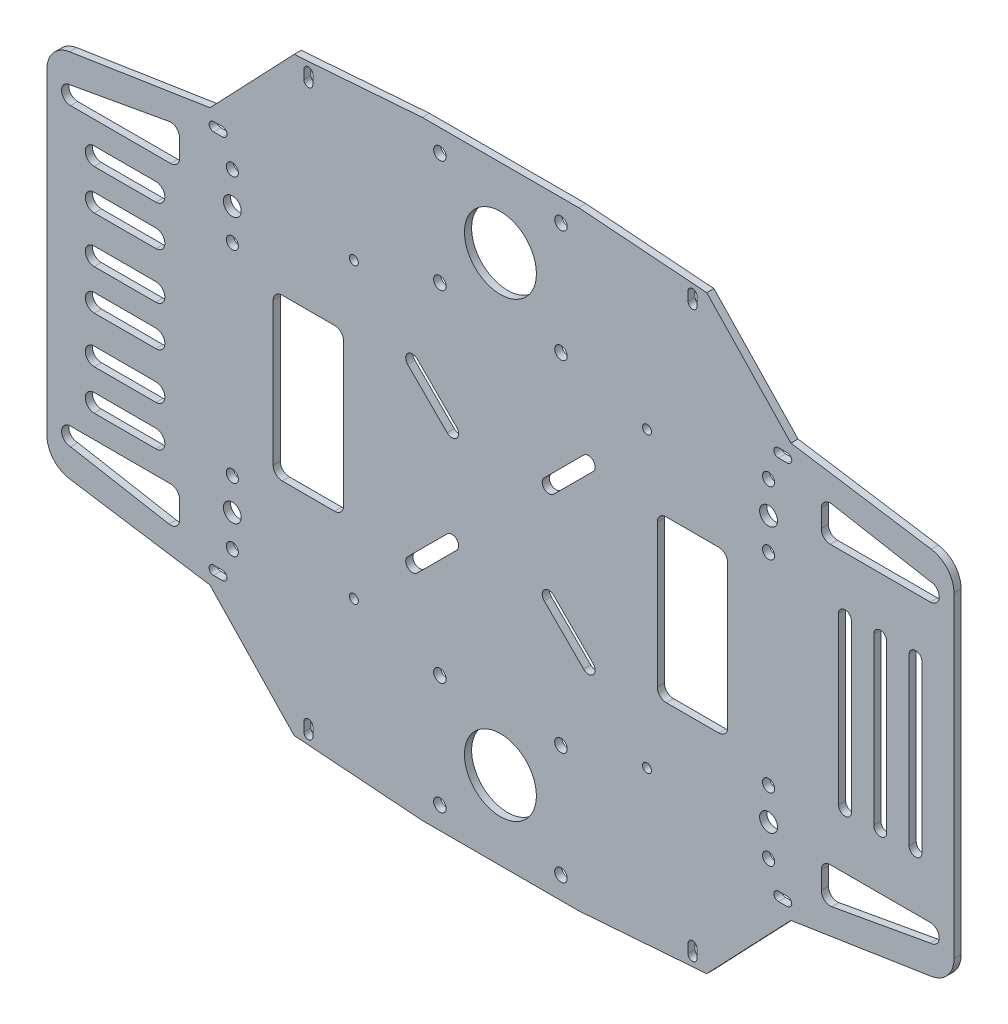
SolidWorks part; units mm, degrees
ref_plane "Front Plane" through (0, 0, 0) normal (0, 0, 1) x (1, 0, 0)
ref_plane "Top Plane" through (0, 0, 0) normal (0, 1, 0) x (1, 0, 0)
ref_plane "Right Plane" through (0, 0, 0) normal (1, 0, 0) x (0, 0, -1)
sketch "Sketch1" plane through (0, 0, 0) normal (0, 0, 1) x (1, 0, 0)
  line L0 (0, 0) -> (0, 68.13) construction
  line L5 (71.9943, -68.13) -> (-71.9943, 68.13) construction
  line L6 (71.9943, 68.13) -> (-71.9943, -68.13) construction
  line L7 (0, 0) -> (0, -68.13) construction
  line L8 (0, 68.13) -> (-46.175, 68.13) construction
  line L9 (0, 68.13) -> (46.175, 68.13) construction
  line L10 (0, 0) -> (46.175, 0) construction
  line L11 (0, 0) -> (-46.175, 0) construction
  line L12 (46.175, 0) -> (46.175, 66) construction
  line L13 (-46.175, 0) -> (-46.175, 66) construction
  line L14 (0, -68.13) -> (-46.175, -68.13) construction
  line L15 (0, -68.13) -> (46.175, -68.13) construction
  line L16 (-46.175, 0) -> (-46.175, -66) construction
  line L17 (46.175, 0) -> (46.175, -66) construction
  line L18 (0, 68.13) -> (-17.5, 68.13)
  line L19 (0, 68.13) -> (17.5, 68.13)
  line L20 (-17.5, 68.13) -> (-46.175, 66)
  line L21 (17.5, 68.13) -> (46.175, 66)
  line L22 (0, -68.13) -> (-17.5, -68.13)
  line L23 (-17.5, -68.13) -> (-46.175, -66)
  line L24 (0, -68.13) -> (17.5, -68.13)
  line L25 (17.5, -68.13) -> (46.175, -66)
  line L26 (46.175, 0) -> (65, 0) construction
  line L27 (-46.175, 0) -> (-65, 0) construction
  line L28 (65, 0) -> (65, 46.25) construction
  line L29 (65, 0) -> (65, -46.25) construction
  line L31 (46.175, -66) -> (65, -46.25)
  line L32 (-65, 0) -> (-65, 46.25) construction
  line L33 (-46.175, 66) -> (-65, 46.25)
  line L34 (-65, 0) -> (-65, -46.25) construction
  line L35 (-65, -46.25) -> (-46.175, -66)
  line L36 (65, 0) -> (101.5, 0) construction
  line L37 (-65, 0) -> (-101.5, 0) construction
  line L38 (-101.5, 0) -> (-101.5, 35.4573)
  line L39 (-65, 46.25) -> (-96.4178, 41.3867)
  line L40 (-101.5, 0) -> (-101.5, -35.4573)
  line L41 (-96.4178, -41.3867) -> (-65, -46.25)
  line L42 (101.5, 0) -> (101.5, 35.4573)
  line L43 (101.5, 0) -> (101.5, -35.4573)
  line L44 (96.4178, -41.3867) -> (65, -46.25)
  line L45 (65, 46.25) -> (96.4178, 41.3867)
  line L46 (46.175, 66) -> (65, 46.25)
  arc A0 (96.4178, -41.3867) -> (101.5, -35.4573) centre (95.5, -35.4573) ccw
  arc A1 (101.5, 35.4573) -> (96.4178, 41.3867) centre (95.5, 35.4573) ccw
  arc A2 (-96.4178, -41.3867) -> (-101.5, -35.4573) centre (-95.5, -35.4573) cw
  arc A3 (-101.5, 35.4573) -> (-96.4178, 41.3867) centre (-95.5, 35.4573) cw
  point P0 (0, 0)
  point P41 (-101.5, -40.6)
  point P44 (-101.5, 40.6)
  dimension "D16" = 6
  dimension "D17" = 6
  dimension "D18" = 6
  dimension "D19" = 6
  dimension "D1" = 136.26
  dimension "D2" = 46.175
  dimension "D3" = 46.175
  dimension "D4" = 66
  dimension "D5" = 66
  dimension "D6" = 17.5
  dimension "D7" = 17.5
  dimension "D8" = 18.825
  dimension "D9" = 18.825
  dimension "D10" = 46.25
  dimension "D11" = 46.25
  dimension "D12" = 36.5
  dimension "D13" = 36.5
  dimension "D14" = 40.6
  dimension "D15" = 40.6
  dimension "D20" = 66
  dimension "D21" = 66
extrude "Boss-Extrude1" add sketch "Sketch1" along normal blind 1.6
ref_plane "Plane1" through (0, 0, 1.6) normal (0, 0, 1) x (1, 0, 0)
sketch "Sketch2" plane through (0, 0, 1.6) normal (0, 0, 1) x (1, 0, 0)
  line L0 (0, 0) -> (0, -38.05) construction
  line L1 (0, -38.05) -> (-13.55, -38.05) construction
  line L2 (0, -38.05) -> (13.55, -38.05) construction
  line L3 (0, 0) -> (0, 38.05) construction
  line L4 (0, 38.05) -> (13.55, 38.05) construction
  line L5 (0, 38.05) -> (-13.55, 38.05) construction
  line L6 (-13.55, 38.05) -> (-13.55, 63.15) construction
  line L7 (13.55, 38.05) -> (13.55, 63.15) construction
  line L8 (-13.55, -38.05) -> (-13.55, -63.15) construction
  line L9 (13.55, -38.05) -> (13.55, -63.15) construction
  line L10 (-13.55, -63.15) -> (13.55, -38.05) construction
  line L11 (-13.55, 38.05) -> (13.55, 63.15) construction
  circle A0 centre (0, -50.6) radius 8.05
  circle A1 centre (0, 50.6) radius 8.05
  circle A2 centre (-13.55, -38.05) radius 1.4
  circle A3 centre (13.55, -38.05) radius 1.4
  circle A4 centre (13.55, -63.15) radius 1.4
  circle A5 centre (-13.55, -63.15) radius 1.4
  circle A6 centre (-13.55, 38.05) radius 1.4
  circle A7 centre (13.55, 38.05) radius 1.4
  circle A8 centre (-13.55, 63.15) radius 1.4
  circle A9 centre (13.55, 63.15) radius 1.4
  dimension "D7" = 16.1
  dimension "D8" = 16.1
  dimension "D9" = 2.8
  dimension "D10" = 2.8
  dimension "D11" = 2.8
  dimension "D12" = 2.8
  dimension "D13" = 2.8
  dimension "D14" = 2.8
  dimension "D15" = 2.8
  dimension "D16" = 2.8
  dimension "D1" = 38.05
  dimension "D2" = 13.55
  dimension "D3" = 13.55
  dimension "D4" = 38.05
  dimension "D5" = 25.1
  dimension "D6" = 25.1
extrude "Cut-Extrude1" cut sketch "Sketch2" against normal blind 1.6
ref_plane "Plane2" through (0, 0, 1.6) normal (0, 0, 1) x (1, 0, 0)
sketch "Sketch3" plane through (0, 0, 1.6) normal (0, 0, 1) x (1, 0, 0)
  line L0 (0, 0) -> (-19.6929, 19.6929) construction
  line L1 (0, 0) -> (-19.6929, -19.6929) construction
  line L2 (0, 0) -> (19.6929, 19.6929) construction
  line L3 (0, 0) -> (19.6929, -19.6929) construction
  line L4 (-19.6929, 19.6929) -> (-20.7536, 18.6323) construction
  line L5 (-20.7536, 18.6323) -> (-11.9147, 9.7934)
  line L6 (-19.6929, 19.6929) -> (-18.6323, 20.7536) construction
  line L7 (-18.6323, 20.7536) -> (-9.7934, 11.9147)
  line L8 (-11.9147, 9.7934) -> (-9.7934, 11.9147) construction
  line L9 (18.6323, 20.7536) -> (9.7934, 11.9147)
  line L10 (20.7536, 18.6323) -> (11.9147, 9.7934)
  line L11 (20.7536, -18.6323) -> (11.9147, -9.7934)
  line L12 (18.6323, -20.7536) -> (9.7934, -11.9147)
  line L13 (-18.6323, -20.7536) -> (-9.7934, -11.9147)
  line L14 (-20.7536, -18.6323) -> (-11.9147, -9.7934)
  line L15 (0, 0) -> (-42.975, 0) construction
  line L16 (35.1, 16) -> (35.1, -16)
  line L17 (-37.1, -18) -> (-48.85, -18)
  line L18 (-35.1, -16) -> (-35.1, 16)
  line L19 (-37.1, 18) -> (-48.85, 18)
  line L20 (-50.85, -16) -> (-50.85, 16)
  line L21 (-35.1, -18) -> (-50.85, 18) construction
  line L22 (-35.1, 18) -> (-50.85, -18) construction
  line L23 (37.1, 18) -> (48.85, 18)
  line L24 (50.85, 16) -> (50.85, -16)
  line L25 (37.1, -18) -> (48.85, -18)
  arc A1 (-18.6323, 20.7536) -> (-20.7536, 18.6323) centre (-19.6929, 19.6929) ccw
  arc A2 (9.7934, 11.9147) -> (11.9147, 9.7934) centre (10.8541, 10.8541) ccw
  arc A3 (-11.9147, 9.7934) -> (-9.7934, 11.9147) centre (-10.8541, 10.8541) ccw
  arc A4 (20.7536, 18.6323) -> (18.6323, 20.7536) centre (19.6929, 19.6929) ccw
  arc A5 (11.9147, -9.7934) -> (9.7934, -11.9147) centre (10.8541, -10.8541) ccw
  arc A6 (18.6323, -20.7536) -> (20.7536, -18.6323) centre (19.6929, -19.6929) ccw
  arc A7 (-9.7934, -11.9147) -> (-11.9147, -9.7934) centre (-10.8541, -10.8541) ccw
  arc A8 (-20.7536, -18.6323) -> (-18.6323, -20.7536) centre (-19.6929, -19.6929) ccw
  arc A9 (-35.1, 16) -> (-37.1, 18) centre (-37.1, 16) ccw
  arc A10 (-37.1, -18) -> (-35.1, -16) centre (-37.1, -16) ccw
  arc A11 (-48.85, -18) -> (-50.85, -16) centre (-48.85, -16) cw
  arc A12 (-50.85, 16) -> (-48.85, 18) centre (-48.85, 16) cw
  arc A13 (37.1, 18) -> (35.1, 16) centre (37.1, 16) ccw
  arc A14 (35.1, -16) -> (37.1, -18) centre (37.1, -16) ccw
  arc A15 (48.85, 18) -> (50.85, 16) centre (48.85, 16) cw
  arc A16 (50.85, -16) -> (48.85, -18) centre (48.85, -16) cw
  point P32 (0, 0)
  point P61 (0, 0)
  dimension "D1" = 12.5
  dimension "D2" = 3
  dimension "D8" = 2
  dimension "D9" = 2
  dimension "D10" = 2
  dimension "D11" = 2
  dimension "D3" = 12.5
  dimension "D5" = 42.975
  dimension "D6" = 15.75
  dimension "D7" = 36
  dimension "D4" = 4
  dimension "D12" = 2
extrude "Cut-Extrude2" cut sketch "Sketch3" against normal blind 1.6
ref_plane "Plane3" through (0, 0, 1.6) normal (0, 0, 1) x (1, 0, 0)
sketch "Sketch4" plane through (0, 0, 1.6) normal (0, 0, 1) x (1, 0, 0)
  line L0 (0, 0) -> (0, 35.05) construction
  line L1 (0, 35.05) -> (84, 35.05) construction
  line L2 (84, 35.05) -> (84, 31.05) construction
  line L3 (84, 35.05) -> (84, 39.05) construction
  line L4 (84, 31.05) -> (73.8, 31.05)
  line L5 (84, 31.05) -> (96.2, 31.05)
  line L6 (71.8, 33.05) -> (71.8, 37.05)
  line L7 (71.8, 35.05) -> (96.2, 35.05) construction
  line L8 (96.2, 35.05) -> (96.2, 31.05) construction
  line L9 (96.2, 35.05) -> (74.1543, 39.0184)
  line L10 (-84, 31.05) -> (-96.2, 31.05)
  line L11 (-84, 31.05) -> (-73.8, 31.05)
  line L12 (-71.8, 33.05) -> (-71.8, 37.05)
  line L13 (-96.2, 35.05) -> (-74.1543, 39.0184)
  line L14 (0, 0) -> (-62.7797, 0) construction
  line L15 (84, -31.05) -> (96.2, -31.05)
  line L16 (84, -31.05) -> (73.8, -31.05)
  line L17 (71.8, -33.05) -> (71.8, -37.05)
  line L18 (96.2, -35.05) -> (74.1543, -39.0184)
  line L19 (-84, -31.05) -> (-73.8, -31.05)
  line L20 (-71.8, -33.05) -> (-71.8, -37.05)
  line L21 (-96.2, -35.05) -> (-74.1543, -39.0184)
  line L22 (-84, -31.05) -> (-96.2, -31.05)
  arc A0 (96.2, 31.05) -> (96.2, 35.05) centre (96.2, 33.05) ccw
  arc A1 (73.8, 31.05) -> (71.8, 33.05) centre (73.8, 33.05) cw
  arc A2 (71.8, 37.05) -> (74.1543, 39.0184) centre (73.8, 37.05) cw
  arc A3 (-73.8, 31.05) -> (-71.8, 33.05) centre (-73.8, 33.05) ccw
  arc A4 (-71.8, 37.05) -> (-74.1543, 39.0184) centre (-73.8, 37.05) ccw
  arc A5 (-96.2, 31.05) -> (-96.2, 35.05) centre (-96.2, 33.05) cw
  arc A6 (73.8, -31.05) -> (71.8, -33.05) centre (73.8, -33.05) ccw
  arc A7 (71.8, -37.05) -> (74.1543, -39.0184) centre (73.8, -37.05) ccw
  arc A8 (96.2, -31.05) -> (96.2, -35.05) centre (96.2, -33.05) cw
  arc A9 (-73.8, -31.05) -> (-71.8, -33.05) centre (-73.8, -33.05) cw
  arc A10 (-71.8, -37.05) -> (-74.1543, -39.0184) centre (-73.8, -37.05) cw
  arc A11 (-96.2, -31.05) -> (-96.2, -35.05) centre (-96.2, -33.05) ccw
  point P15 (71.8, 31.05)
  dimension "D7" = 2
  dimension "D8" = 2
  dimension "D1" = 35.05
  dimension "D2" = 84
  dimension "D3" = 4
  dimension "D4" = 4
  dimension "D5" = 12.2
  dimension "D6" = 12.2
extrude "Cut-Extrude3" cut sketch "Sketch4" against normal blind 1.6
ref_plane "Plane4" through (0, 0, 1.6) normal (0, 0, 1) x (1, 0, 0)
sketch "Sketch5" plane through (0, 0, 1.6) normal (0, 0, 1) x (1, 0, 0)
  line L0 (0, 0) -> (-84, 0) construction
  line L1 (-84, 0) -> (-84, 4.5) construction
  line L2 (-90.9, 16.9) -> (-77.1, 16.9)
  line L3 (-90.9, 6.5) -> (-77.1, 6.5)
  line L5 (-90.9, 2.5) -> (-77.1, 2.5)
  line L7 (-90.9, 6.5) -> (-77.1, 2.5) construction
  line L8 (-90.9, 2.5) -> (-77.1, 6.5) construction
  line L9 (-90.9, 12.9) -> (-77.1, 12.9)
  line L10 (-90.9, 25.9) -> (-77.1, 25.9)
  line L11 (-90.9, 21.9) -> (-77.1, 21.9)
  line L12 (-90.9, -2.5) -> (-77.1, -2.5)
  line L13 (-90.9, -6.5) -> (-77.1, -6.5)
  line L14 (-90.9, -12.9) -> (-77.1, -12.9)
  line L15 (-90.9, -16.9) -> (-77.1, -16.9)
  line L16 (-90.9, -21.9) -> (-77.1, -21.9)
  line L17 (-90.9, -25.9) -> (-77.1, -25.9)
  arc A0 (-77.1, 2.5) -> (-77.1, 6.5) centre (-77.1, 4.5) ccw
  arc A1 (-90.9, 6.5) -> (-90.9, 2.5) centre (-90.9, 4.5) ccw
  arc A2 (-77.1, 12.9) -> (-77.1, 16.9) centre (-77.1, 14.9) ccw
  arc A3 (-90.9, 16.9) -> (-90.9, 12.9) centre (-90.9, 14.9) ccw
  arc A4 (-77.1, 21.9) -> (-77.1, 25.9) centre (-77.1, 23.9) ccw
  arc A5 (-90.9, 25.9) -> (-90.9, 21.9) centre (-90.9, 23.9) ccw
  arc A6 (-90.9, -6.5) -> (-90.9, -2.5) centre (-90.9, -4.5) cw
  arc A7 (-77.1, -2.5) -> (-77.1, -6.5) centre (-77.1, -4.5) cw
  arc A8 (-90.9, -16.9) -> (-90.9, -12.9) centre (-90.9, -14.9) cw
  arc A9 (-77.1, -12.9) -> (-77.1, -16.9) centre (-77.1, -14.9) cw
  arc A10 (-90.9, -25.9) -> (-90.9, -21.9) centre (-90.9, -23.9) cw
  arc A11 (-77.1, -21.9) -> (-77.1, -25.9) centre (-77.1, -23.9) cw
  dimension "D1" = 84
  dimension "D2" = 4.5
  dimension "D3" = 4
  dimension "D4" = 13.8
  dimension "D5" = 2
  dimension "D6" = 2
extrude "Cut-Extrude4" cut sketch "Sketch5" against normal blind 1.6
ref_plane "Plane5" through (0, 0, 1.6) normal (0, 0, 1) x (1, 0, 0)
sketch "Sketch6" plane through (0, 0, 1.6) normal (0, 0, 1) x (1, 0, 0)
  line L0 (0, 0) -> (85, 0) construction
  line L6 (85, 0) -> (92.9, 0) construction
  line L11 (86.45, -18.55) -> (86.45, 18.55)
  line L14 (83.55, -18.55) -> (83.55, 18.55)
  line L15 (78.55, -18.55) -> (78.55, 18.55)
  line L16 (75.65, -18.55) -> (75.65, 18.55)
  line L19 (94.35, -18.55) -> (94.35, 18.55)
  line L21 (91.45, -18.55) -> (91.45, 18.55)
  arc A8 (86.45, 18.55) -> (83.55, 18.55) centre (85, 18.55) ccw
  arc A9 (83.55, -18.55) -> (86.45, -18.55) centre (85, -18.55) ccw
  arc A10 (94.35, 18.55) -> (91.45, 18.55) centre (92.9, 18.55) ccw
  arc A11 (91.45, -18.55) -> (94.35, -18.55) centre (92.9, -18.55) ccw
  arc A12 (78.55, 18.55) -> (75.65, 18.55) centre (77.1, 18.55) ccw
  arc A13 (75.65, -18.55) -> (78.55, -18.55) centre (77.1, -18.55) ccw
  dimension "D3" = 7.9
  dimension "D1" = 2.9
  dimension "D2" = 37.1
  dimension "D4" = 2.9
extrude "Cut-Extrude5" cut sketch "Sketch6" against normal blind 1.6
ref_plane "Plane6" through (0, 0, 1.6) normal (0, 0, 1) x (1, 0, 0)
sketch "Sketch7" plane through (0, 0, 1.6) normal (0, 0, 1) x (1, 0, 0)
  line L0 (0, 0) -> (-32.804, 32.804) construction
  line L1 (0, 0) -> (32.804, 32.804) construction
  line L2 (0, 0) -> (-32.804, -32.804) construction
  line L3 (0, 0) -> (32.804, -32.804) construction
  line L4 (-32.804, 32.804) -> (-49.2052, 49.2052) construction
  line L8 (-64.1951, 42.9821) -> (-42.9819, 64.1952) construction
  line L9 (-42.9819, 64.1952) -> (-32.804, 32.804) construction
  line L10 (-32.804, 32.804) -> (-64.1951, 42.9821) construction
  line L11 (-64.1951, 43.9821) -> (-62.1951, 43.9821)
  line L12 (-64.1769, 41.9822) -> (-62.2133, 41.9822)
  line L13 (-43.9819, 64.1952) -> (-43.9819, 62.1952)
  line L14 (-41.9819, 64.1952) -> (-41.9819, 62.1952)
  line L15 (64.1952, 41.9819) -> (62.1952, 41.9819)
  line L16 (64.1952, 43.9819) -> (62.1952, 43.9819)
  line L17 (41.9822, 64.1769) -> (41.9822, 62.2133)
  line L18 (43.9821, 64.1951) -> (43.9821, 62.1951)
  line L19 (41.9819, -64.1952) -> (41.9819, -62.1952)
  line L20 (43.9819, -64.1952) -> (43.9819, -62.1952)
  line L21 (64.1769, -41.9822) -> (62.2133, -41.9822)
  line L22 (64.1951, -43.9821) -> (62.1951, -43.9821)
  line L23 (-64.1952, -41.9819) -> (-62.1952, -41.9819)
  line L24 (-64.1952, -43.9819) -> (-62.1952, -43.9819)
  line L25 (-41.9822, -64.1769) -> (-41.9822, -62.2133)
  line L26 (-43.9821, -64.1951) -> (-43.9821, -62.1951)
  circle A1 centre (-32.804, 32.804) radius 1
  arc A5 (-64.1951, 43.9821) -> (-64.1769, 41.9822) centre (-64.1951, 42.9821) ccw
  arc A6 (-41.9819, 64.1952) -> (-43.9819, 64.1952) centre (-42.9819, 64.1952) ccw
  arc A7 (-62.2133, 41.9822) -> (-62.1951, 43.9821) centre (-62.1951, 42.9821) ccw
  arc A8 (-43.9819, 62.1952) -> (-41.9819, 62.1952) centre (-42.9819, 62.1952) ccw
  arc A9 (62.1952, 43.9819) -> (62.1952, 41.9819) centre (62.1952, 42.9819) ccw
  arc A10 (64.1952, 41.9819) -> (64.1952, 43.9819) centre (64.1952, 42.9819) ccw
  arc A11 (41.9822, 62.2133) -> (43.9821, 62.1951) centre (42.9821, 62.1951) ccw
  arc A12 (43.9821, 64.1951) -> (41.9822, 64.1769) centre (42.9821, 64.1951) ccw
  circle A13 centre (32.804, 32.804) radius 1
  arc A14 (43.9819, -62.1952) -> (41.9819, -62.1952) centre (42.9819, -62.1952) ccw
  arc A15 (41.9819, -64.1952) -> (43.9819, -64.1952) centre (42.9819, -64.1952) ccw
  arc A16 (62.2133, -41.9822) -> (62.1951, -43.9821) centre (62.1951, -42.9821) ccw
  arc A17 (64.1951, -43.9821) -> (64.1769, -41.9822) centre (64.1951, -42.9821) ccw
  circle A18 centre (32.804, -32.804) radius 1
  arc A19 (-62.1952, -43.9819) -> (-62.1952, -41.9819) centre (-62.1952, -42.9819) ccw
  arc A20 (-64.1952, -41.9819) -> (-64.1952, -43.9819) centre (-64.1952, -42.9819) ccw
  arc A21 (-41.9822, -62.2133) -> (-43.9821, -62.1951) centre (-42.9821, -62.1951) ccw
  arc A22 (-43.9821, -64.1951) -> (-41.9822, -64.1769) centre (-42.9821, -64.1951) ccw
  circle A23 centre (-32.804, -32.804) radius 1
  point P65 (0, 0)
  dimension "D1" = 33
  dimension "D5" = 2
  dimension "D6" = 2
  dimension "D7" = 2
  dimension "D2" = 2
  dimension "D3" = 33
  dimension "D4" = 2
  dimension "D8" = 4
extrude "Cut-Extrude6" cut sketch "Sketch7" against normal blind 1.6
ref_plane "Plane7" through (0, 0, 1.6) normal (0, 0, 1) x (1, 0, 0)
sketch "Sketch8" plane through (0, 0, 1.6) normal (0, 0, 1) x (1, 0, 0)
  line L0 (0, 0) -> (60, 0) construction
  line L1 (60, 0) -> (60, 22.58) construction
  line L2 (60, 22.58) -> (60, 29.68) construction
  line L3 (60, 29.68) -> (60, 36.78) construction
  line L4 (0, 0) -> (0, 42.55) construction
  circle A0 centre (60, 22.58) radius 1.35
  circle A1 centre (60, 29.68) radius 2
  circle A2 centre (60, 36.78) radius 1.35
  circle A3 centre (60, -22.58) radius 1.35
  circle A4 centre (60, -29.68) radius 2
  circle A5 centre (60, -36.78) radius 1.35
  circle A6 centre (0, 50.6) radius 8.05 construction
  circle A7 centre (-60, -36.78) radius 1.35
  circle A8 centre (-60, -22.58) radius 1.35
  circle A9 centre (-60, -29.68) radius 2
  circle A10 centre (-60, 22.58) radius 1.35
  circle A11 centre (-60, 29.68) radius 2
  circle A12 centre (-60, 36.78) radius 1.35
  dimension "D3" = 2.7
  dimension "D5" = 4
  dimension "D7" = 2.7
  dimension "D1" = 60
  dimension "D2" = 22.58
  dimension "D4" = 7.1
  dimension "D6" = 7.1
extrude "Cut-Extrude7" cut sketch "Sketch8" against normal blind 10
